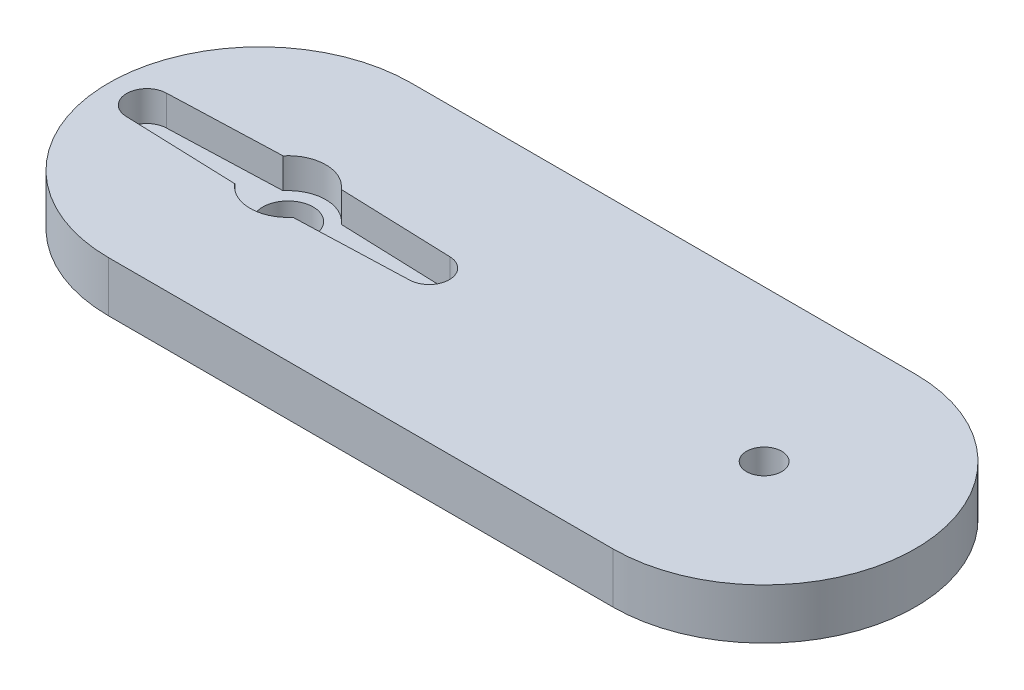
SolidWorks part; units mm, degrees
material "ABS"
ref_plane "Plano frontal" through (0, 0, 0) normal (0, 0, 1) x (1, 0, 0)
ref_plane "Plano superior" through (0, 0, 0) normal (0, 1, 0) x (1, 0, 0)
ref_plane "Plano direito" through (0, 0, 0) normal (1, 0, 0) x (0, 0, -1)
sketch "Esboço3" plane through (0, 0, 0) normal (0, 1, 0) x (1, 0, 0)
  line L2 (-50, 15) -> (0, 15)
  line L3 (-50, -15) -> (0, -15)
  arc A0 (0, 15) -> (0, -15) centre (0, 0) cw
  arc A1 (-50, 15) -> (-50, -15) centre (-50, 0) ccw
  point P4 (0, 0)
  dimension "D2" = 30
  dimension "D4" = 15
  dimension "D1" = 50
  dimension "D5" = 50
extrude "Ressalto-extrusão2" add sketch "Esboço3" along normal blind 5
sketch "Esboço4" plane through (0, 5, 0) normal (0, 1, 0) x (1, 0, 0)
  line L0 (-65, 0) -> (15, 0) construction
  arc A0 (-50, 15) -> (-50, -15) centre (-50, 0) ccw construction
  arc A1 (0, -15) -> (0, 15) centre (0, 0) ccw construction
  circle A3 centre (0, 0) radius 1.75
  dimension "D1" = 3.5
extrude "Corte-extrusão1" cut sketch "Esboço4" against normal blind 10
sketch "Esboço6" plane through (0, 5, 0) normal (0, 1, 0) x (1, 0, 0)
  line L0 (-46.9774, 2.4891) -> (-47.2106, 2.4974)
  line L1 (-61.2815, 1.9987) -> (-50.0961, 2.3951)
  line L2 (-61.2815, -1.9987) -> (-50.0961, -2.3951)
  line L3 (-33.1398, -1.9987) -> (-44.3252, -2.3951)
  line L4 (-33.1398, 1.9987) -> (-44.3252, 2.3951)
  line L5 (0, 15) -> (-50, 15) construction
  line L6 (-50, -15) -> (0, -15) construction
  line L7 (-47.4439, 2.4891) -> (-47.2106, 2.4974)
  line L8 (-47.4439, -2.4891) -> (-47.2106, -2.4974)
  line L9 (-46.9774, -2.4891) -> (-47.2106, -2.4974)
  arc A0 (-50.0961, -2.3951) -> (-44.3252, -2.3951) centre (-47.2106, 0) ccw
  circle A1 centre (-47.2106, 0) radius 2.5
  arc A2 (-61.1776, -1.9997) -> (-61.2815, 1.9987) centre (-61.2106, 0) cw
  arc A3 (-33.2436, -1.9997) -> (-33.1398, 1.9987) centre (-33.2106, 0) ccw
  arc A4 (-44.3252, 2.3951) -> (-50.0961, 2.3951) centre (-47.2106, 0) ccw
  arc A8 (-50, 15) -> (-50, -15) centre (-50, 0) ccw construction
  dimension "D1" = 28
  dimension "D3" = 47.2106
  dimension "D9" = 2
  dimension "D10" = 2
  dimension "D2" = 2.7894
  dimension "D5" = 4.7902
  dimension "D4" = 30
  dimension "D6" = 3.9998
  dimension "D7" = 3.9975
  dimension "D8" = 4.7902
extrude "Corte-extrusão2" cut sketch "Esboço6" against normal blind 3
sketch "Esboço7" plane through (0, 5, 0) normal (0, 1, 0) x (1, 0, 0)
  circle A0 centre (-47.2106, 0) radius 2.5
extrude "Corte-extrusão3" cut sketch "Esboço7" against normal through all
